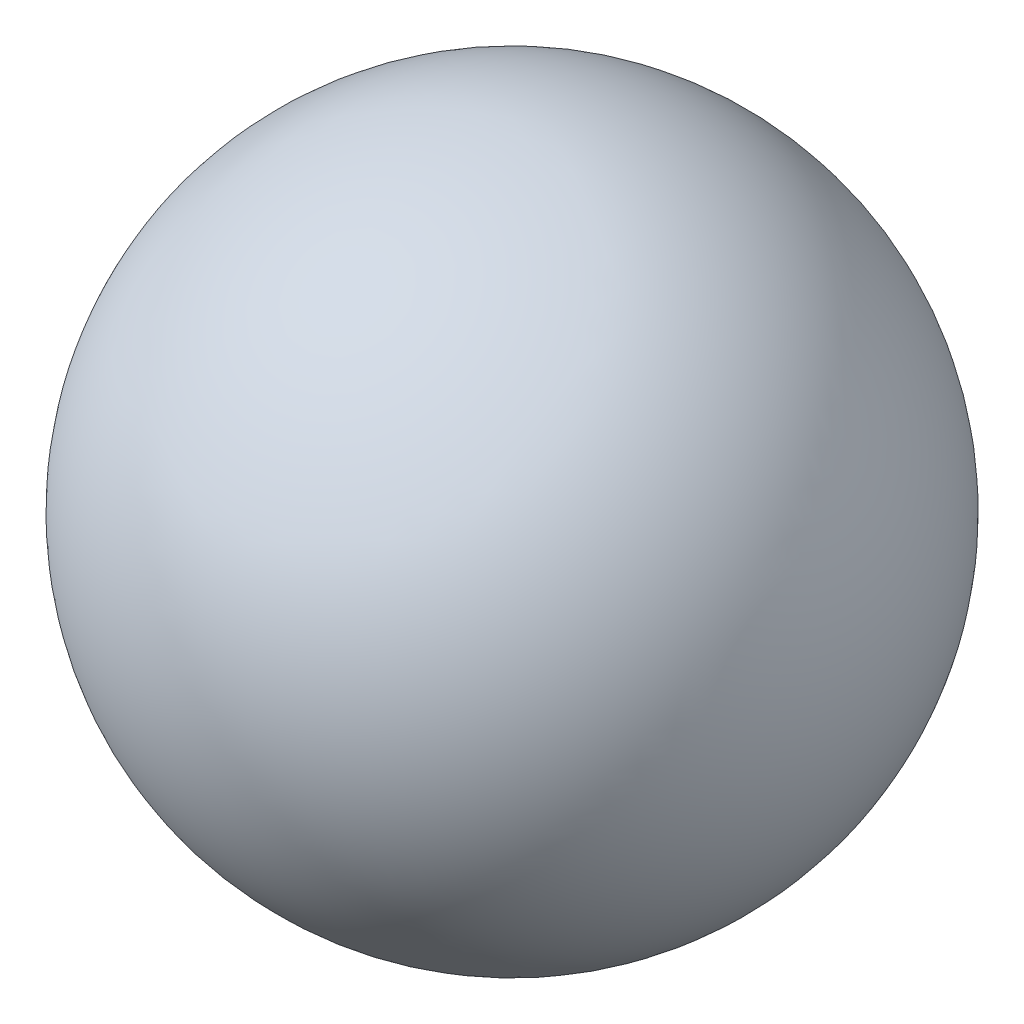
SolidWorks part; units mm, degrees
ref_plane "Plan1" through (0, 0, 0) normal (0, 0, 1) x (1, 0, 0)
ref_plane "Plan2" through (0, 0, 0) normal (0, 1, 0) x (1, 0, 0)
ref_plane "Plan3" through (0, 0, 0) normal (1, 0, 0) x (0, 0, -1)
sketch "Esquisse1" plane through (0, 0, 0) normal (0, 1, 0) x (1, 0, 0)
  line L1 (-0.3, 3.95) -> (7.7, 3.95) construction
  line L2 (-0.3, 7.9) -> (-0.3, 0) construction
  line L3 (7.7, 7.9) -> (7.7, 0) construction
  line L4 (1.15, 3.95) -> (6.25, 3.95)
  circle A1 centre (3.7, 3.95) radius 2.55 construction
  arc A2 (6.25, 3.95) -> (1.15, 3.95) centre (3.7, 3.95) ccw
revolve "Base-Révolution" add sketch "Esquisse1" angle 360 about L1
